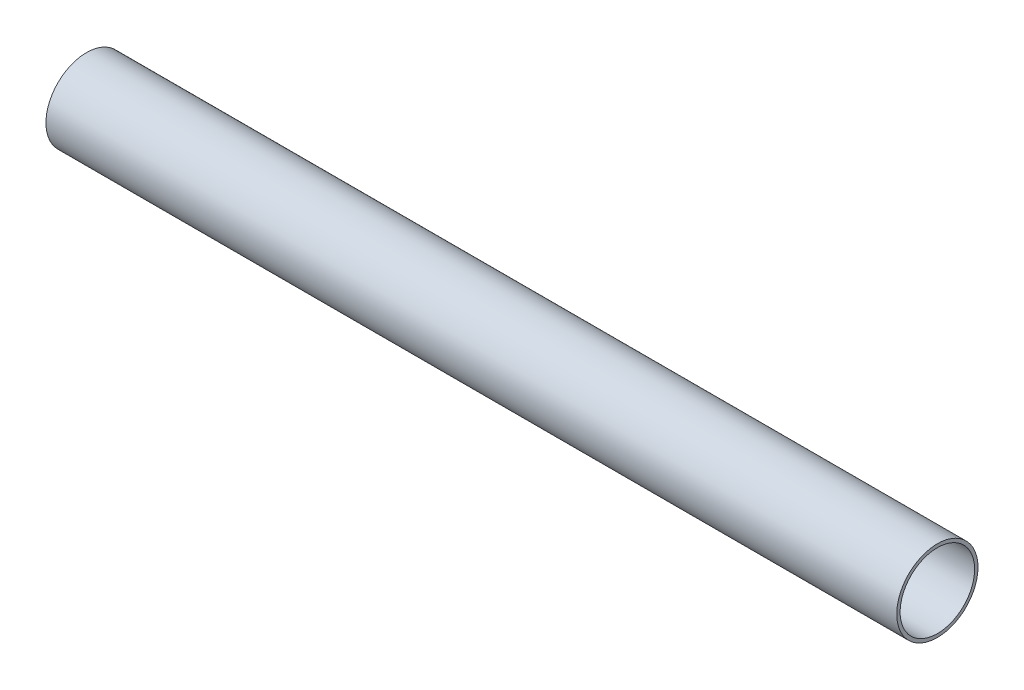
SolidWorks part; units mm, degrees
material "Rubber"
ref_plane "Front Plane" through (0, 0, 0) normal (0, 0, 1) x (1, 0, 0)
ref_plane "Top Plane" through (0, 0, 0) normal (0, 1, 0) x (1, 0, 0)
ref_plane "Right Plane" through (0, 0, 0) normal (1, 0, 0) x (0, 0, -1)
sketch "Sketch1" plane through (0, 0, 0) normal (1, 0, 0) x (0, 0, -1)
  circle A0 centre (0, 0) radius 17.4625
  circle A1 centre (0, 0) radius 19.05
  dimension "D1" = 34.925
  dimension "D2" = 38.1
extrude "Boss-Extrude1" add sketch "Sketch1" along normal blind 398.8308
